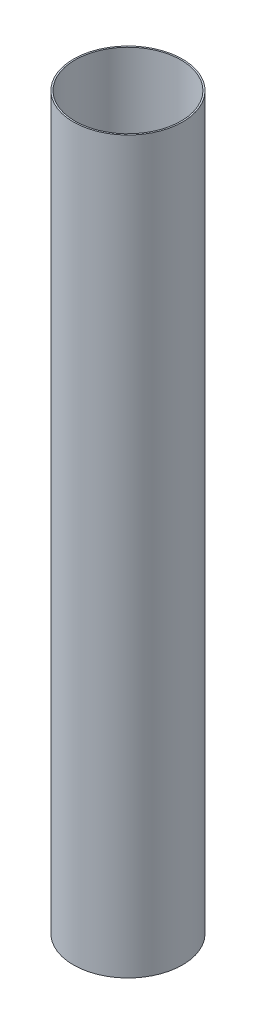
SolidWorks part; units mm, degrees
ref_plane "Front" through (0, 0, 0) normal (0, 0, 1) x (1, 0, 0)
ref_plane "Top" through (0, 0, 0) normal (0, 1, 0) x (1, 0, 0)
ref_plane "Right" through (0, 0, 0) normal (1, 0, 0) x (0, 0, -1)
sketch "Sketch1" plane through (0, 0, 0) normal (0, 1, 0) x (1, 0, 0)
  circle A0 centre (0, 0) radius 7.8359
  circle A1 centre (0, 0) radius 7.62
extrude "Boss-Extrude1" add sketch "Sketch1" along normal blind 104.902
